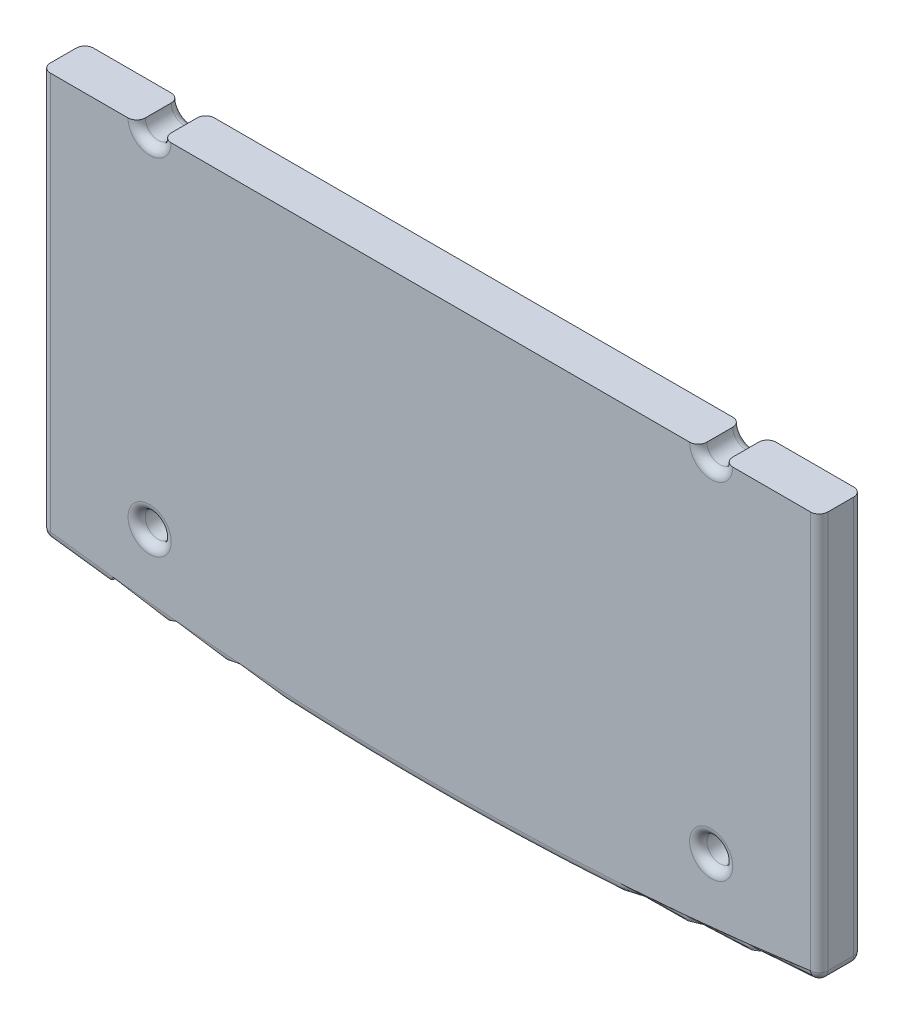
SolidWorks part; units mm, degrees
ref_plane "Front Plane" through (0, 0, 0) normal (0, 0, 1) x (1, 0, 0)
ref_plane "Top Plane" through (0, 0, 0) normal (0, 1, 0) x (1, 0, 0)
ref_plane "Right Plane" through (0, 0, 0) normal (1, 0, 0) x (0, 0, -1)
sketch "Sketch2" plane through (0, 0, 0) normal (0, 0, 1) x (1, 0, 0)
  line L1 (90, 86.2696) -> (-90, 86.2696)
  line L2 (90, 86.2696) -> (90, -93.7304)
  line L3 (90, -93.7304) -> (-90, -93.7304)
  line L4 (-90, 86.2696) -> (-90, -93.7304)
  arc A0 (-90, 86.2696) -> (90, 86.2696) centre (0, -201.8302) cw
  arc A1 (90, -93.7304) -> (-90, -93.7304) centre (0, 549.1136) cw
  point P5 (0, 86.2696)
  point P7 (0, 100)
  point P9 (0, -100)
  dimension "D1" = 180
  dimension "D2" = 180
  dimension "D3" = 0
  dimension "D4" = 100
  dimension "D5" = 100
extrude "Boss-Extrude1" add sketch "Sketch2" along normal blind 10 contours L1 L4 L3 L2 | A0 L1 | A1 L3
sketch "Sketch3" plane through (0, 0, 0) normal (0, 0, 1) x (1, 0, 0)
  line L0 (90, 86.2696) -> (90, -93.7304) construction
  line L1 (90, 70) -> (75, 70)
  line L2 (90, 70) -> (90, 20)
  line L3 (90, 20) -> (75, 20)
  line L4 (75, 70) -> (75, 20)
  point P6 (90, 45)
  dimension "D1" = 50
  dimension "D2" = 15
  dimension "D3" = 45
sketch "Sketch4" plane through (0, 0, 0) normal (0, 0, 1) x (1, 0, 0)
  circle A0 centre (-65, 0) radius 3
  dimension "D1" = 0
  dimension "D2" = 65
extrude "Cut-Extrude4" cut sketch "Sketch4" along normal blind 10
pattern_linear "LPattern2" count 2 spacing 130 along (1, 0, 0) count 2 spacing 80 along (0, -1, 0) of "Cut-Extrude4"
pattern_linear "LPattern3" count 2 spacing 80 along (0, 1, 0) of "LPattern2", "Cut-Extrude4"
fillet "Fillet1" radius 2 24 edges at (-90, -93.7304, 5) (68, -80, 10) (68, -80, 0) (-62, -80, 10) (-62, -80, 0) (0, -100, 0) (0, -100, 10) (-90, -3.7304, 0) (-90, -3.7304, 10) (-62, 0, 10) (-62, 0, 0) (68, 0, 10) (68, 0, 0) (-62, 80, 10) (-62, 80, 0) (68, 80, 10) (68, 80, 0) (90, -93.7304, 5) (90, -3.7304, 0) (90, -3.7304, 10) (90, 86.2696, 5) (0, 100, 0) (0, 100, 10) (-90, 86.2696, 5)
sketch "Sketch5" plane through (0, 0, 10) normal (0, 0, 1) x (1, 0, 0)
  line L1 (-102.315, 113.6856) -> (124.5518, 113.6856)
  line L2 (-102.315, 113.6856) -> (-102.315, 0)
  line L3 (-102.315, 0) -> (124.5518, 0)
  line L4 (124.5518, 113.6856) -> (124.5518, 0)
extrude "Cut-Extrude5" cut sketch "Sketch5" against normal blind 10
